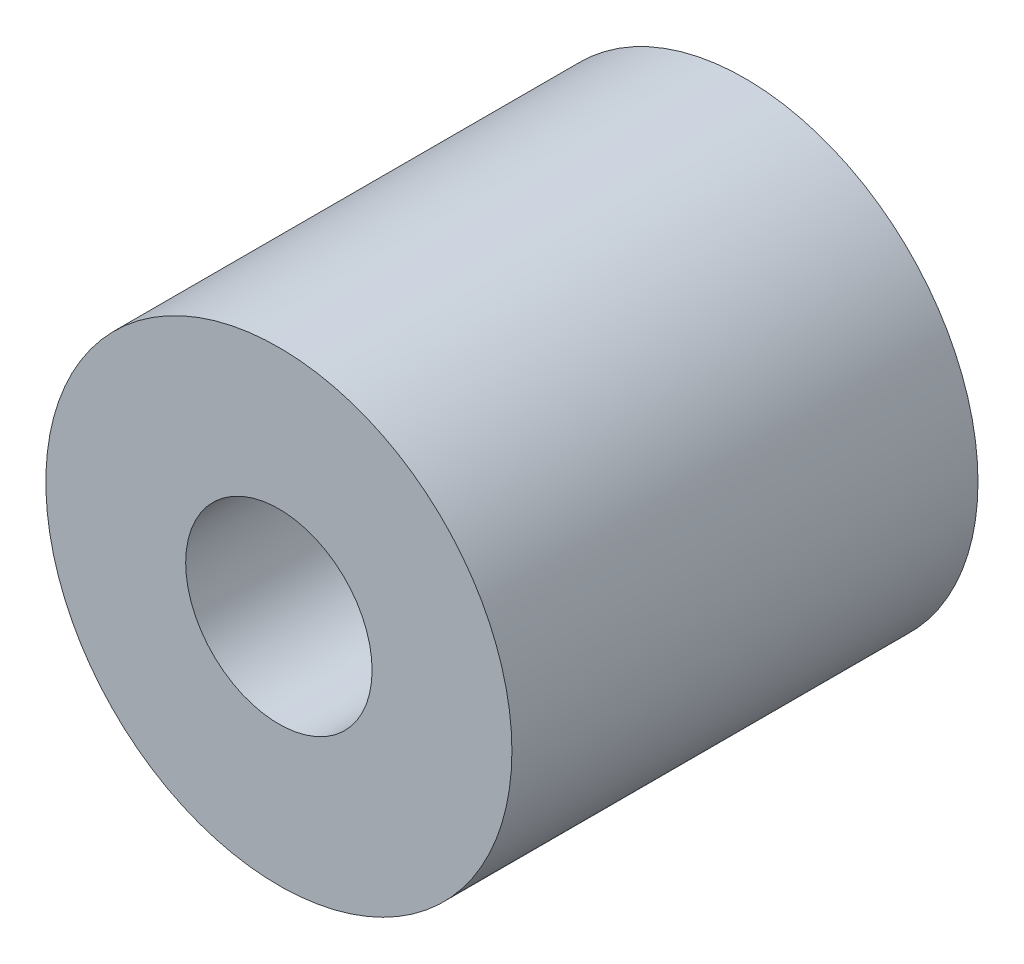
SolidWorks part; units mm, degrees
ref_plane "Front" through (0, 0, 0) normal (0, 0, 1) x (1, 0, 0)
ref_plane "Top" through (0, 0, 0) normal (0, 1, 0) x (1, 0, 0)
ref_plane "Right" through (0, 0, 0) normal (1, 0, 0) x (0, 0, -1)
sketch "Эскиз1" plane through (0, 0, 0) normal (0, 0, 1) x (1, 0, 0)
  circle A0 centre (0, 0) radius 1.6
  circle A1 centre (0, 0) radius 4
extrude "Бобышка-Вытянуть1" add sketch "Эскиз1" along normal blind 8
